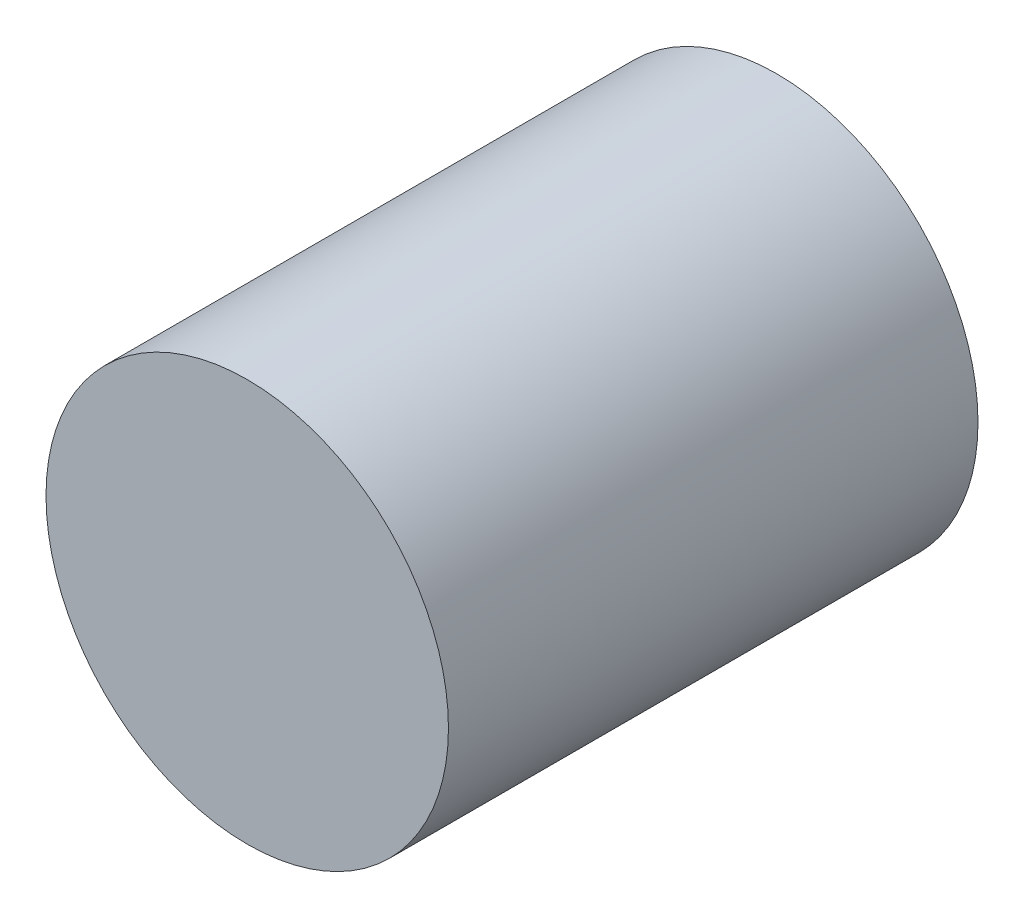
SolidWorks part; units mm, degrees
ref_plane "Front Plane" through (0, 0, 0) normal (0, 0, 1) x (1, 0, 0)
ref_plane "Top Plane" through (0, 0, 0) normal (0, 1, 0) x (1, 0, 0)
ref_plane "Right Plane" through (0, 0, 0) normal (1, 0, 0) x (0, 0, -1)
sketch "Sketch1" plane through (0, 0, 0) normal (0, 0, 1) x (1, 0, 0)
  circle A0 centre (0, 0) radius 4.826
  dimension "D1" = 9.652
extrude "Boss-Extrude1" add sketch "Sketch1" along normal blind 12.7
